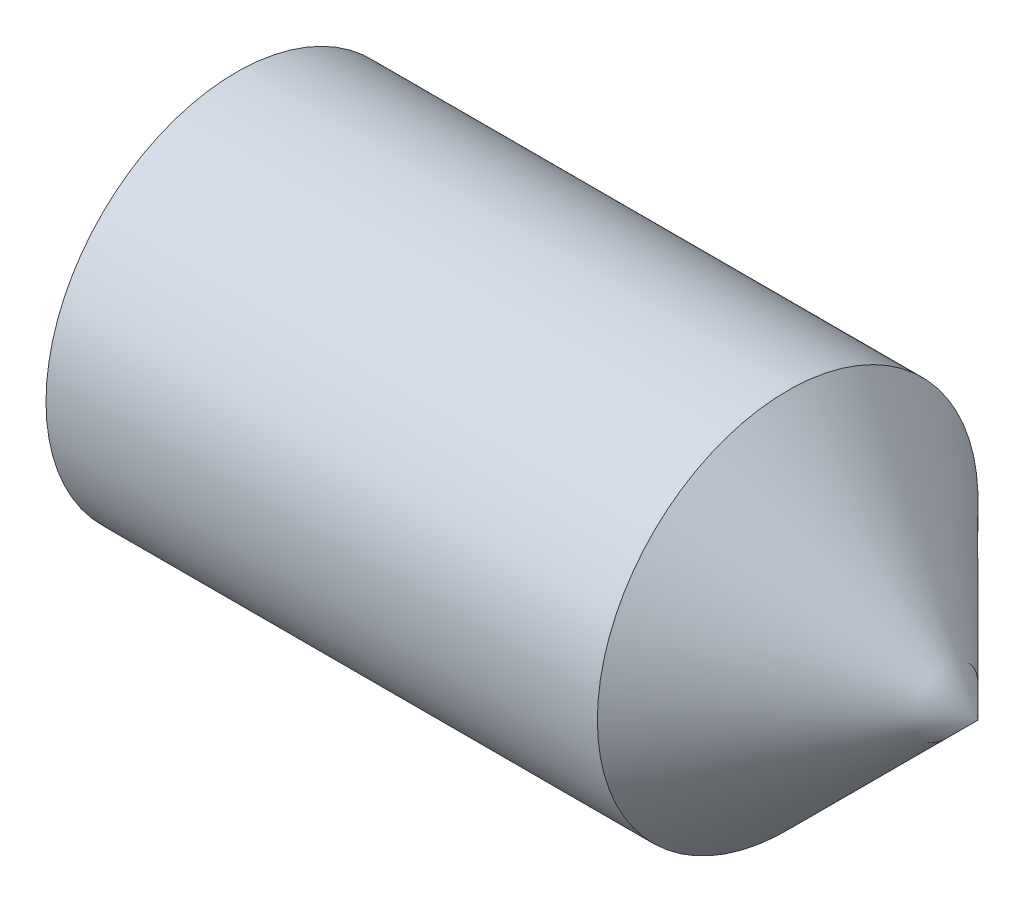
SolidWorks part; units mm, degrees
revolve "BaseBody" add sketch "BodySke" angle 360 about L5
sketch "BodySke" plane through (0, 0, 0) normal (0, 0, 1) x (1, 0, 0)
  line L0 (0, 0) -> (0, 2.055)
  line L1 (0, 2.055) -> (0.2569, 2.5)
  line L2 (0.2569, 2.5) -> (7.5, 2.5)
  line L3 (7.5, 2.5) -> (10, 0)
  line L4 (10, 0) -> (0, 0)
  line L5 (-12.7, 0) -> (88.9, 0) construction
  line L6 (7.5, -2.5) -> (10, 0) construction
  line L7 (0.4, 15.875) -> (0.4, -3.175) construction
  line L8 (0, -2.055) -> (0.2569, -2.5) construction
  dimension "Diameter" = 5
  dimension "Drive_ch_ang" = 60
  dimension "Minor_dia" = 4.11
  dimension "Advance" = 0.8
  dimension "Cone_ang" = 90
  dimension "Length" = 10
cosmetic thread "ThreadCosmetic" [suppressed] parameters "Thread_minor"=4.11
ref_plane "Plane1" through (0, 0, 0) normal (0, 0, 1) x (1, 0, 0)
ref_plane "Plane2" through (0, 0, 0) normal (0, 1, 0) x (1, 0, 0)
ref_plane "Plane3" through (0, 0, 0) normal (1, 0, 0) x (0, 0, -1)
sketch "Sketch2" plane through (0, 0, 0) normal (-1, 0, 0) x (0, 0, 1)
  line L0 (0.7217, 1.25) -> (-0.7217, 1.25)
  line L1 (-0.7217, 1.25) -> (-1.4434, 0)
  line L2 (0.7217, 1.25) -> (1.4434, 0)
  line L3 (0.7217, -1.25) -> (1.4434, 0)
  line L4 (0.7217, -1.25) -> (-0.7217, -1.25)
  line L5 (-0.7217, -1.25) -> (-1.4434, 0)
  dimension "Hex_size" = 2.5
  dimension "D2" = 1.25
  dimension "D3" = 1.25
extrude "Hex" cut sketch "Sketch2" against normal blind 3
sketch "ThdSchSke" plane through (0, 0, 0) normal (0, 0, 1) x (1, 0, 0)
  line L0 (0.2569, -2.055) -> (-0.0547, -2.5)
  line L1 (0.2569, -2.055) -> (0.5685, -2.5)
  line L2 (0.5685, -2.5) -> (0.5685, -3.125)
  line L3 (-3.175, 0) -> (5.1513, 0) construction
  line L4 (0.2569, 2.5) -> (0.2569, -2.5) construction
  line L5 (0.5685, -3.125) -> (-0.0547, -3.125)
  line L6 (-0.0547, -3.125) -> (-0.0547, -2.5)
  dimension "Thread_minor" = 4.11
  dimension "Diameter" = 5
revolve "ThreadSchematic" [suppressed] cut sketch "ThdSchSke" angle 360 about L3
pattern_linear "ThdSchPat" [suppressed]
equation "\"D2@Sketch2\" = \"Hex_size@Sketch2\" / 2"
equation "\"D3@Sketch2\" = \"Hex_size@Sketch2\" / 2"
equation "\"Thread_minor@ThreadCosmetic\" = \"Minor_dia@BodySke\""
equation "\"Thread_minor@ThdSchSke\" = \"Thread_minor@ThreadCosmetic\""
equation "\"Diameter@ThdSchSke\" = \"Diameter@BodySke\""
equation "\"Overcut@ThdSchSke\" = \"Diameter@BodySke\" * 1.25"
equation "\"Num_threads@ThdSchPat\" = int( (\"Length@BodySke\" - ( ( ( \"Diameter@BodySke\" - \"Minor_dia@BodySke\" ) * 0.5 ) / tan( \"Drive_ch_ang@BodySke\" * 0.017453292 ) ) - ( ( \"Diameter@BodySke\" * 0.5 ) / tan( \"Cone_ang@BodySke\" * 0.008726646 ) ) ) / \"Advance@BodySke\" + 0.999 )  + 1"
equation "\"Advance@ThdSchPat\" = (\"Length@BodySke\" - ( ( ( \"Diameter@BodySke\" - \"Minor_dia@BodySke\" ) * 0.5 ) / tan( \"Drive_ch_ang@BodySke\" * 0.017453292 ) ) - ( ( \"Diameter@BodySke\" * 0.5 ) / tan( \"Cone_ang@BodySke\" * 0.008726646 ) ) ) /  (\"Num_threads@ThdSchPat\" - 1) 'relax it"
equation "' \"Num_threads@ThdSchPat\" = \"Num_threads@ThdSchPat\" - sgn( \"Num_threads@ThdSchPat\" - 1) '---chamfered tips only---"
